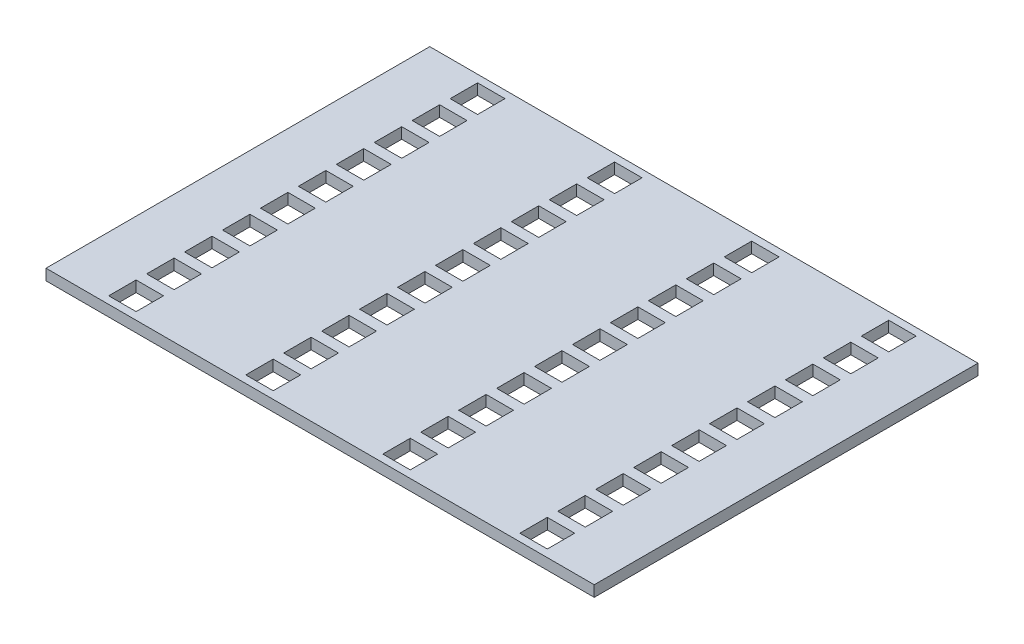
SolidWorks part; units mm, degrees
ref_plane "Front Plane" through (0, 0, 0) normal (0, 0, 1) x (1, 0, 0)
ref_plane "Top Plane" through (0, 0, 0) normal (0, 1, 0) x (1, 0, 0)
ref_plane "Right Plane" through (0, 0, 0) normal (1, 0, 0) x (0, 0, -1)
sketch "Sketch1" plane through (0, 0, 0) normal (0, 1, 0) x (1, 0, 0)
  line L1 (-72.5, 58.0208) -> (27.5, 58.0208)
  line L2 (-72.5, 58.0208) -> (-72.5, -11.9792)
  line L3 (-72.5, -11.9792) -> (27.5, -11.9792)
  line L4 (27.5, 58.0208) -> (27.5, -11.9792)
  line L5 (-72.5, 58.0208) -> (27.5, -11.9792) construction
  line L6 (-72.5, -11.9792) -> (27.5, 58.0208) construction
  point P0 (-22.5, 23.0208)
  dimension "D1" = 70
  dimension "D2" = 100
extrude "Boss-Extrude1" add sketch "Sketch1" along normal blind 2
sketch "Sketch2" plane through (0, 2, 0) normal (0, 1, 0) x (1, 0, 0)
  line L0 (27.5, 58.0208) -> (-72.5, 58.0208) construction
  line L1 (-37.4222, 51.6608) -> (-37.4222, 56.6608)
  line L2 (-37.4222, 51.6608) -> (-32.4222, 51.6608)
  line L3 (-62.4222, 51.6608) -> (-57.4222, 51.6608)
  line L4 (-62.4222, 51.6608) -> (-62.4222, 56.6608)
  line L5 (-62.4222, 56.6608) -> (-57.4222, 56.6608)
  line L6 (-57.4222, 51.6608) -> (-57.4222, 56.6608)
  line L7 (-32.4222, 51.6608) -> (-32.4222, 56.6608)
  line L8 (-62.4222, 51.6608) -> (-57.4222, 56.6608) construction
  line L9 (-62.4222, 56.6608) -> (-57.4222, 51.6608) construction
  line L10 (-37.4222, 56.6608) -> (-32.4222, 56.6608)
  line L11 (-37.4222, 56.6608) -> (-32.4222, 51.6608) construction
  line L12 (-37.4222, 51.6608) -> (-32.4222, 56.6608) construction
  line L13 (-12.4222, 51.6608) -> (-12.4222, 56.6608)
  line L14 (-12.4222, 51.6608) -> (-7.4222, 51.6608)
  line L15 (-7.4222, 51.6608) -> (-7.4222, 56.6608)
  line L16 (-12.4222, 56.6608) -> (-7.4222, 56.6608)
  line L17 (-12.4222, 56.6608) -> (-7.4222, 51.6608) construction
  line L18 (-12.4222, 51.6608) -> (-7.4222, 56.6608) construction
  line L19 (12.5778, 51.6608) -> (12.5778, 56.6608)
  line L20 (12.5778, 51.6608) -> (17.5778, 51.6608)
  line L21 (17.5778, 51.6608) -> (17.5778, 56.6608)
  line L22 (12.5778, 56.6608) -> (17.5778, 56.6608)
  line L23 (12.5778, 56.6608) -> (17.5778, 51.6608) construction
  line L24 (12.5778, 51.6608) -> (17.5778, 56.6608) construction
  line L25 (-37.4222, 44.7408) -> (-37.4222, 49.7408)
  line L26 (-37.4222, 44.7408) -> (-32.4222, 44.7408)
  line L27 (-32.4222, 44.7408) -> (-32.4222, 49.7408)
  line L28 (-37.4222, 49.7408) -> (-32.4222, 49.7408)
  line L29 (-37.4222, 49.7408) -> (-32.4222, 44.7408) construction
  line L30 (-37.4222, 44.7408) -> (-32.4222, 49.7408) construction
  line L31 (-12.4222, 44.7408) -> (-12.4222, 49.7408)
  line L32 (-12.4222, 44.7408) -> (-7.4222, 44.7408)
  line L33 (-7.4222, 44.7408) -> (-7.4222, 49.7408)
  line L34 (-12.4222, 49.7408) -> (-7.4222, 49.7408)
  line L35 (-12.4222, 49.7408) -> (-7.4222, 44.7408) construction
  line L36 (-12.4222, 44.7408) -> (-7.4222, 49.7408) construction
  line L37 (12.5778, 44.7408) -> (12.5778, 49.7408)
  line L38 (12.5778, 44.7408) -> (17.5778, 44.7408)
  line L39 (17.5778, 44.7408) -> (17.5778, 49.7408)
  line L40 (12.5778, 49.7408) -> (17.5778, 49.7408)
  line L41 (12.5778, 49.7408) -> (17.5778, 44.7408) construction
  line L42 (12.5778, 44.7408) -> (17.5778, 49.7408) construction
  line L43 (-37.4222, 37.8208) -> (-37.4222, 42.8208)
  line L44 (-37.4222, 37.8208) -> (-32.4222, 37.8208)
  line L45 (-32.4222, 37.8208) -> (-32.4222, 42.8208)
  line L46 (-37.4222, 42.8208) -> (-32.4222, 42.8208)
  line L47 (-37.4222, 42.8208) -> (-32.4222, 37.8208) construction
  line L48 (-37.4222, 37.8208) -> (-32.4222, 42.8208) construction
  line L49 (-12.4222, 37.8208) -> (-12.4222, 42.8208)
  line L50 (-12.4222, 37.8208) -> (-7.4222, 37.8208)
  line L51 (-7.4222, 37.8208) -> (-7.4222, 42.8208)
  line L52 (-12.4222, 42.8208) -> (-7.4222, 42.8208)
  line L53 (-12.4222, 42.8208) -> (-7.4222, 37.8208) construction
  line L54 (-12.4222, 37.8208) -> (-7.4222, 42.8208) construction
  line L55 (12.5778, 37.8208) -> (12.5778, 42.8208)
  line L56 (12.5778, 37.8208) -> (17.5778, 37.8208)
  line L57 (17.5778, 37.8208) -> (17.5778, 42.8208)
  line L58 (12.5778, 42.8208) -> (17.5778, 42.8208)
  line L59 (12.5778, 42.8208) -> (17.5778, 37.8208) construction
  line L60 (12.5778, 37.8208) -> (17.5778, 42.8208) construction
  line L61 (-37.4222, 30.9008) -> (-37.4222, 35.9008)
  line L62 (-37.4222, 30.9008) -> (-32.4222, 30.9008)
  line L63 (-32.4222, 30.9008) -> (-32.4222, 35.9008)
  line L64 (-37.4222, 35.9008) -> (-32.4222, 35.9008)
  line L65 (-37.4222, 35.9008) -> (-32.4222, 30.9008) construction
  line L66 (-37.4222, 30.9008) -> (-32.4222, 35.9008) construction
  line L67 (-12.4222, 30.9008) -> (-12.4222, 35.9008)
  line L68 (-12.4222, 30.9008) -> (-7.4222, 30.9008)
  line L69 (-7.4222, 30.9008) -> (-7.4222, 35.9008)
  line L70 (-12.4222, 35.9008) -> (-7.4222, 35.9008)
  line L71 (-12.4222, 35.9008) -> (-7.4222, 30.9008) construction
  line L72 (-12.4222, 30.9008) -> (-7.4222, 35.9008) construction
  line L73 (12.5778, 30.9008) -> (12.5778, 35.9008)
  line L74 (12.5778, 30.9008) -> (17.5778, 30.9008)
  line L75 (17.5778, 30.9008) -> (17.5778, 35.9008)
  line L76 (12.5778, 35.9008) -> (17.5778, 35.9008)
  line L77 (12.5778, 35.9008) -> (17.5778, 30.9008) construction
  line L78 (12.5778, 30.9008) -> (17.5778, 35.9008) construction
  line L79 (-37.4222, 23.9808) -> (-37.4222, 28.9808)
  line L80 (-37.4222, 23.9808) -> (-32.4222, 23.9808)
  line L81 (-32.4222, 23.9808) -> (-32.4222, 28.9808)
  line L82 (-37.4222, 28.9808) -> (-32.4222, 28.9808)
  line L83 (-37.4222, 28.9808) -> (-32.4222, 23.9808) construction
  line L84 (-37.4222, 23.9808) -> (-32.4222, 28.9808) construction
  line L85 (-12.4222, 23.9808) -> (-12.4222, 28.9808)
  line L86 (-12.4222, 23.9808) -> (-7.4222, 23.9808)
  line L87 (-7.4222, 23.9808) -> (-7.4222, 28.9808)
  line L88 (-12.4222, 28.9808) -> (-7.4222, 28.9808)
  line L89 (-12.4222, 28.9808) -> (-7.4222, 23.9808) construction
  line L90 (-12.4222, 23.9808) -> (-7.4222, 28.9808) construction
  line L91 (12.5778, 23.9808) -> (12.5778, 28.9808)
  line L92 (12.5778, 23.9808) -> (17.5778, 23.9808)
  line L93 (17.5778, 23.9808) -> (17.5778, 28.9808)
  line L94 (12.5778, 28.9808) -> (17.5778, 28.9808)
  line L95 (12.5778, 28.9808) -> (17.5778, 23.9808) construction
  line L96 (12.5778, 23.9808) -> (17.5778, 28.9808) construction
  line L97 (-37.4222, 17.0608) -> (-37.4222, 22.0608)
  line L98 (-37.4222, 17.0608) -> (-32.4222, 17.0608)
  line L99 (-32.4222, 17.0608) -> (-32.4222, 22.0608)
  line L100 (-37.4222, 22.0608) -> (-32.4222, 22.0608)
  line L101 (-37.4222, 22.0608) -> (-32.4222, 17.0608) construction
  line L102 (-37.4222, 17.0608) -> (-32.4222, 22.0608) construction
  line L103 (-12.4222, 17.0608) -> (-12.4222, 22.0608)
  line L104 (-12.4222, 17.0608) -> (-7.4222, 17.0608)
  line L105 (-7.4222, 17.0608) -> (-7.4222, 22.0608)
  line L106 (-12.4222, 22.0608) -> (-7.4222, 22.0608)
  line L107 (-12.4222, 22.0608) -> (-7.4222, 17.0608) construction
  line L108 (-12.4222, 17.0608) -> (-7.4222, 22.0608) construction
  line L109 (12.5778, 17.0608) -> (12.5778, 22.0608)
  line L110 (12.5778, 17.0608) -> (17.5778, 17.0608)
  line L111 (17.5778, 17.0608) -> (17.5778, 22.0608)
  line L112 (12.5778, 22.0608) -> (17.5778, 22.0608)
  line L113 (12.5778, 22.0608) -> (17.5778, 17.0608) construction
  line L114 (12.5778, 17.0608) -> (17.5778, 22.0608) construction
  line L115 (-37.4222, 10.1408) -> (-37.4222, 15.1408)
  line L116 (-37.4222, 10.1408) -> (-32.4222, 10.1408)
  line L117 (-32.4222, 10.1408) -> (-32.4222, 15.1408)
  line L118 (-37.4222, 15.1408) -> (-32.4222, 15.1408)
  line L119 (-37.4222, 15.1408) -> (-32.4222, 10.1408) construction
  line L120 (-37.4222, 10.1408) -> (-32.4222, 15.1408) construction
  line L121 (-12.4222, 10.1408) -> (-12.4222, 15.1408)
  line L122 (-12.4222, 10.1408) -> (-7.4222, 10.1408)
  line L123 (-7.4222, 10.1408) -> (-7.4222, 15.1408)
  line L124 (-12.4222, 15.1408) -> (-7.4222, 15.1408)
  line L125 (-12.4222, 15.1408) -> (-7.4222, 10.1408) construction
  line L126 (-12.4222, 10.1408) -> (-7.4222, 15.1408) construction
  line L127 (12.5778, 10.1408) -> (12.5778, 15.1408)
  line L128 (12.5778, 10.1408) -> (17.5778, 10.1408)
  line L129 (17.5778, 10.1408) -> (17.5778, 15.1408)
  line L130 (12.5778, 15.1408) -> (17.5778, 15.1408)
  line L131 (12.5778, 15.1408) -> (17.5778, 10.1408) construction
  line L132 (12.5778, 10.1408) -> (17.5778, 15.1408) construction
  line L133 (-37.4222, 3.2208) -> (-37.4222, 8.2208)
  line L134 (-37.4222, 3.2208) -> (-32.4222, 3.2208)
  line L135 (-32.4222, 3.2208) -> (-32.4222, 8.2208)
  line L136 (-37.4222, 8.2208) -> (-32.4222, 8.2208)
  line L137 (-37.4222, 8.2208) -> (-32.4222, 3.2208) construction
  line L138 (-37.4222, 3.2208) -> (-32.4222, 8.2208) construction
  line L139 (-12.4222, 3.2208) -> (-12.4222, 8.2208)
  line L140 (-12.4222, 3.2208) -> (-7.4222, 3.2208)
  line L141 (-7.4222, 3.2208) -> (-7.4222, 8.2208)
  line L142 (-12.4222, 8.2208) -> (-7.4222, 8.2208)
  line L143 (-12.4222, 8.2208) -> (-7.4222, 3.2208) construction
  line L144 (-12.4222, 3.2208) -> (-7.4222, 8.2208) construction
  line L145 (12.5778, 3.2208) -> (12.5778, 8.2208)
  line L146 (12.5778, 3.2208) -> (17.5778, 3.2208)
  line L147 (17.5778, 3.2208) -> (17.5778, 8.2208)
  line L148 (12.5778, 8.2208) -> (17.5778, 8.2208)
  line L149 (12.5778, 8.2208) -> (17.5778, 3.2208) construction
  line L150 (12.5778, 3.2208) -> (17.5778, 8.2208) construction
  line L151 (-37.4222, -3.6992) -> (-37.4222, 1.3008)
  line L152 (-37.4222, -3.6992) -> (-32.4222, -3.6992)
  line L153 (-32.4222, -3.6992) -> (-32.4222, 1.3008)
  line L154 (-37.4222, 1.3008) -> (-32.4222, 1.3008)
  line L155 (-37.4222, 1.3008) -> (-32.4222, -3.6992) construction
  line L156 (-37.4222, -3.6992) -> (-32.4222, 1.3008) construction
  line L157 (-12.4222, -3.6992) -> (-12.4222, 1.3008)
  line L158 (-12.4222, -3.6992) -> (-7.4222, -3.6992)
  line L159 (-7.4222, -3.6992) -> (-7.4222, 1.3008)
  line L160 (-12.4222, 1.3008) -> (-7.4222, 1.3008)
  line L161 (-12.4222, 1.3008) -> (-7.4222, -3.6992) construction
  line L162 (-12.4222, -3.6992) -> (-7.4222, 1.3008) construction
  line L163 (12.5778, -3.6992) -> (12.5778, 1.3008)
  line L164 (12.5778, -3.6992) -> (17.5778, -3.6992)
  line L165 (17.5778, -3.6992) -> (17.5778, 1.3008)
  line L166 (12.5778, 1.3008) -> (17.5778, 1.3008)
  line L167 (12.5778, 1.3008) -> (17.5778, -3.6992) construction
  line L168 (12.5778, -3.6992) -> (17.5778, 1.3008) construction
  line L169 (-37.4222, -10.6192) -> (-37.4222, -5.6192)
  line L170 (-37.4222, -10.6192) -> (-32.4222, -10.6192)
  line L171 (-32.4222, -10.6192) -> (-32.4222, -5.6192)
  line L172 (-37.4222, -5.6192) -> (-32.4222, -5.6192)
  line L173 (-37.4222, -5.6192) -> (-32.4222, -10.6192) construction
  line L174 (-37.4222, -10.6192) -> (-32.4222, -5.6192) construction
  line L175 (-12.4222, -10.6192) -> (-12.4222, -5.6192)
  line L176 (-12.4222, -10.6192) -> (-7.4222, -10.6192)
  line L177 (-7.4222, -10.6192) -> (-7.4222, -5.6192)
  line L178 (-12.4222, -5.6192) -> (-7.4222, -5.6192)
  line L179 (-12.4222, -5.6192) -> (-7.4222, -10.6192) construction
  line L180 (-12.4222, -10.6192) -> (-7.4222, -5.6192) construction
  line L181 (12.5778, -10.6192) -> (12.5778, -5.6192)
  line L182 (12.5778, -10.6192) -> (17.5778, -10.6192)
  line L183 (17.5778, -10.6192) -> (17.5778, -5.6192)
  line L184 (12.5778, -5.6192) -> (17.5778, -5.6192)
  line L185 (12.5778, -5.6192) -> (17.5778, -10.6192) construction
  line L186 (12.5778, -10.6192) -> (17.5778, -5.6192) construction
  line L187 (-62.4222, 44.7408) -> (-62.4222, 49.7408)
  line L188 (-62.4222, 44.7408) -> (-57.4222, 44.7408)
  line L189 (-57.4222, 44.7408) -> (-57.4222, 49.7408)
  line L190 (-62.4222, 49.7408) -> (-57.4222, 49.7408)
  line L191 (-62.4222, 49.7408) -> (-57.4222, 44.7408) construction
  line L192 (-62.4222, 44.7408) -> (-57.4222, 49.7408) construction
  line L193 (-62.4222, 37.8208) -> (-62.4222, 42.8208)
  line L194 (-62.4222, 37.8208) -> (-57.4222, 37.8208)
  line L195 (-57.4222, 37.8208) -> (-57.4222, 42.8208)
  line L196 (-62.4222, 42.8208) -> (-57.4222, 42.8208)
  line L197 (-62.4222, 42.8208) -> (-57.4222, 37.8208) construction
  line L198 (-62.4222, 37.8208) -> (-57.4222, 42.8208) construction
  line L199 (-62.4222, 30.9008) -> (-62.4222, 35.9008)
  line L200 (-62.4222, 30.9008) -> (-57.4222, 30.9008)
  line L201 (-57.4222, 30.9008) -> (-57.4222, 35.9008)
  line L202 (-62.4222, 35.9008) -> (-57.4222, 35.9008)
  line L203 (-62.4222, 35.9008) -> (-57.4222, 30.9008) construction
  line L204 (-62.4222, 30.9008) -> (-57.4222, 35.9008) construction
  line L205 (-62.4222, 23.9808) -> (-62.4222, 28.9808)
  line L206 (-62.4222, 23.9808) -> (-57.4222, 23.9808)
  line L207 (-57.4222, 23.9808) -> (-57.4222, 28.9808)
  line L208 (-62.4222, 28.9808) -> (-57.4222, 28.9808)
  line L209 (-62.4222, 28.9808) -> (-57.4222, 23.9808) construction
  line L210 (-62.4222, 23.9808) -> (-57.4222, 28.9808) construction
  line L211 (-62.4222, 17.0608) -> (-62.4222, 22.0608)
  line L212 (-62.4222, 17.0608) -> (-57.4222, 17.0608)
  line L213 (-57.4222, 17.0608) -> (-57.4222, 22.0608)
  line L214 (-62.4222, 22.0608) -> (-57.4222, 22.0608)
  line L215 (-62.4222, 22.0608) -> (-57.4222, 17.0608) construction
  line L216 (-62.4222, 17.0608) -> (-57.4222, 22.0608) construction
  line L217 (-62.4222, 10.1408) -> (-62.4222, 15.1408)
  line L218 (-62.4222, 10.1408) -> (-57.4222, 10.1408)
  line L219 (-57.4222, 10.1408) -> (-57.4222, 15.1408)
  line L220 (-62.4222, 15.1408) -> (-57.4222, 15.1408)
  line L221 (-62.4222, 15.1408) -> (-57.4222, 10.1408) construction
  line L222 (-62.4222, 10.1408) -> (-57.4222, 15.1408) construction
  line L223 (-62.4222, 3.2208) -> (-62.4222, 8.2208)
  line L224 (-62.4222, 3.2208) -> (-57.4222, 3.2208)
  line L225 (-57.4222, 3.2208) -> (-57.4222, 8.2208)
  line L226 (-62.4222, 8.2208) -> (-57.4222, 8.2208)
  line L227 (-62.4222, 8.2208) -> (-57.4222, 3.2208) construction
  line L228 (-62.4222, 3.2208) -> (-57.4222, 8.2208) construction
  line L229 (-62.4222, -3.6992) -> (-62.4222, 1.3008)
  line L230 (-62.4222, -3.6992) -> (-57.4222, -3.6992)
  line L231 (-57.4222, -3.6992) -> (-57.4222, 1.3008)
  line L232 (-62.4222, 1.3008) -> (-57.4222, 1.3008)
  line L233 (-62.4222, 1.3008) -> (-57.4222, -3.6992) construction
  line L234 (-62.4222, -3.6992) -> (-57.4222, 1.3008) construction
  line L235 (-62.4222, -10.6192) -> (-62.4222, -5.6192)
  line L236 (-62.4222, -10.6192) -> (-57.4222, -10.6192)
  line L237 (-57.4222, -10.6192) -> (-57.4222, -5.6192)
  line L238 (-62.4222, -5.6192) -> (-57.4222, -5.6192)
  line L239 (-62.4222, -5.6192) -> (-57.4222, -10.6192) construction
  line L240 (-62.4222, -10.6192) -> (-57.4222, -5.6192) construction
  point P0 (-59.9222, 54.1608)
  point P1 (-59.9222, 54.1608)
  point P17 (-60, 58.0208)
  dimension "D1" = 5
  dimension "D2" = 5
  dimension "D3" = 1.36
  dimension "D4" = 4
  dimension "D5" = 10
extrude "Cut-Extrude1" cut sketch "Sketch2" against normal blind 10
